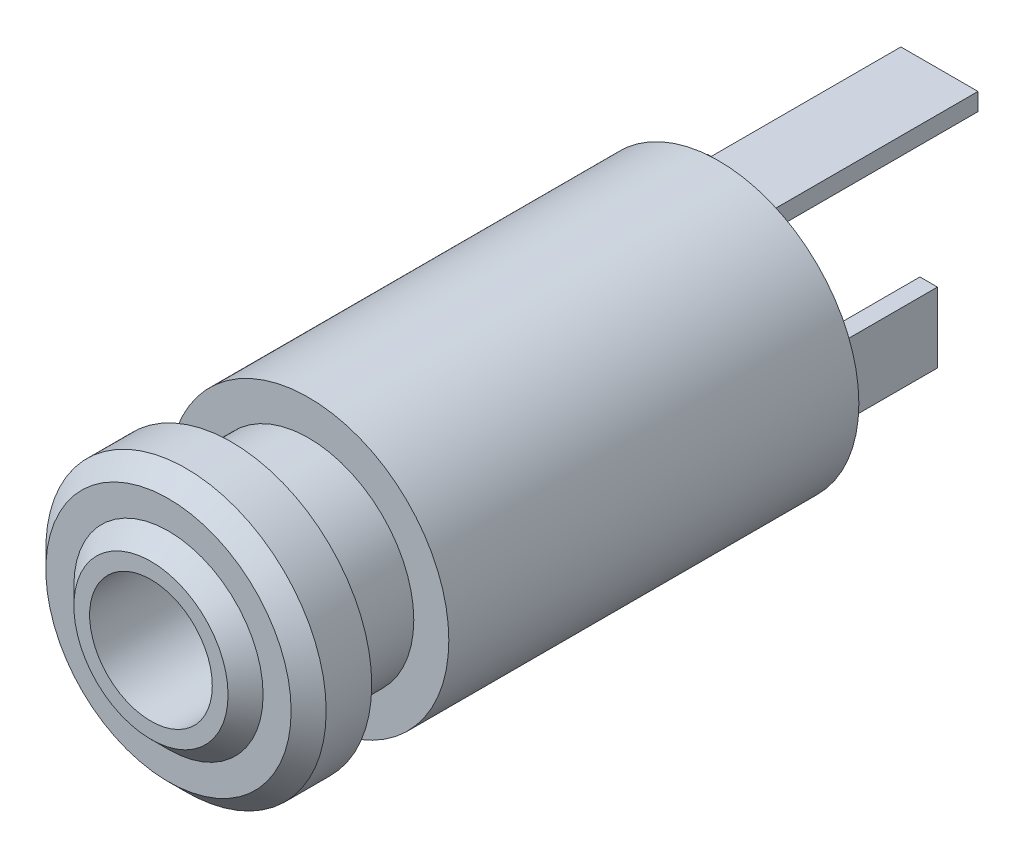
SolidWorks part; units mm, degrees
ref_plane "Front Plane" through (0, 0, 0) normal (0, 0, 1) x (1, 0, 0)
ref_plane "Top Plane" through (0, 0, 0) normal (0, 1, 0) x (1, 0, 0)
ref_plane "Right Plane" through (0, 0, 0) normal (1, 0, 0) x (0, 0, -1)
sketch "Sketch1" plane through (0, 0, 0) normal (1, 0, 0) x (0, 0, -1)
  line L0 (0, 1.75) -> (0, 2.2)
  line L1 (0.8, 3) -> (4.5, 3)
  line L2 (4.5, 3) -> (4.5, 4)
  line L3 (4.5, 4) -> (16.2, 4)
  line L4 (16.2, 4) -> (16.2, 0)
  line L5 (16.2, 0) -> (13.5084, 0)
  line L6 (-3.9851, 0) -> (0, 0) construction
  line L7 (0, 2.2) -> (0.8, 3)
  line L8 (0, 1.75) -> (13.5084, 1.75)
  line L9 (13.5084, 1.75) -> (13.5084, 0)
  point P1 (0, 3)
  dimension "D1" = 6
  dimension "D2" = 8
  dimension "D3" = 4.5
  dimension "D4" = 11.7
  dimension "D5" = 3.5
revolve "Revolve1" add sketch "Sketch1" angle 360 about L6
sketch "Sketch2" plane through (0, 0, 0) normal (0, 0, 1) x (1, 0, 0)
  circle A0 centre (0, 0) radius 2.6
  circle A1 centre (0, 0) radius 4
  dimension "D1" = 8
  dimension "D2" = 5.2
extrude "Boss-Extrude1" add sketch "Sketch2" against normal blind 1.8 from offset 0.5 offset against normal yes
chamfer "Chamfer1" distance 0.5 angle 45 1 edges at (4, 0, -0.5)
sketch "Sketch3" plane through (0, 0, -16.2) normal (0, 0, -1) x (-1, 0, 0)
  line L0 (-3.2432, 1) -> (-3.2432, -1)
  line L1 (-3.2432, 1) -> (-2.7432, 1)
  line L2 (-3.2432, -1) -> (-2.7432, -1)
  line L3 (-2.7432, 1) -> (-2.7432, -1)
  line L4 (-3.2432, 1) -> (-2.7432, -1) construction
  line L5 (-3.2432, -1) -> (-2.7432, 1) construction
  line L6 (-1.1, 3.1128) -> (1.1, 3.1128)
  line L7 (-1.1, 3.1128) -> (-1.1, 2.6128)
  line L8 (1.1, 3.1128) -> (1.1, 2.6128)
  line L9 (-1.1, 2.6128) -> (1.1, 2.6128)
  line L10 (-1.1, 3.1128) -> (1.1, 2.6128) construction
  line L11 (1.1, 3.1128) -> (-1.1, 2.6128) construction
  line L12 (2.6738, 1) -> (2.6738, -1)
  line L13 (2.6738, 1) -> (3.3126, 1)
  line L14 (2.6738, -1) -> (3.3126, -1)
  line L15 (3.3126, 1) -> (3.3126, -1)
  line L16 (2.6738, 1) -> (3.3126, -1) construction
  line L17 (2.6738, -1) -> (3.3126, 1) construction
  line L18 (-2.9932, 0) -> (2.9932, 0) construction
  line L20 (0, 2.8628) -> (0, 0) construction
  point P1 (-2.9932, 0)
  point P2 (0, 2.8628)
  point P3 (2.9932, 0)
  dimension "D1" = 2.2
  dimension "D2" = 2
  dimension "D3" = 0.5
extrude "Boss-Extrude2" add sketch "Sketch3" along normal blind 3
sketch "Sketch4" plane through (0, 0, -19.2) normal (0, 0, -1) x (-1, 0, 0)
  line L4 (-1.1, 3.1128) -> (-1.1, 2.6128)
  line L5 (-1.1, 2.6128) -> (1.1, 2.6128)
  line L6 (1.1, 2.6128) -> (1.1, 3.1128)
  line L7 (1.1, 3.1128) -> (-1.1, 3.1128)
  line L8 (-1.1, 3.1128) -> (-1.1, 2.6128)
  line L9 (-1.1, 2.6128) -> (1.1, 2.6128)
  line L10 (1.1, 2.6128) -> (1.1, 3.1128)
  line L11 (1.1, 3.1128) -> (-1.1, 3.1128)
  dimension "D1" = 0
extrude "Boss-Extrude3" add sketch "Sketch4" along normal blind 3.3
